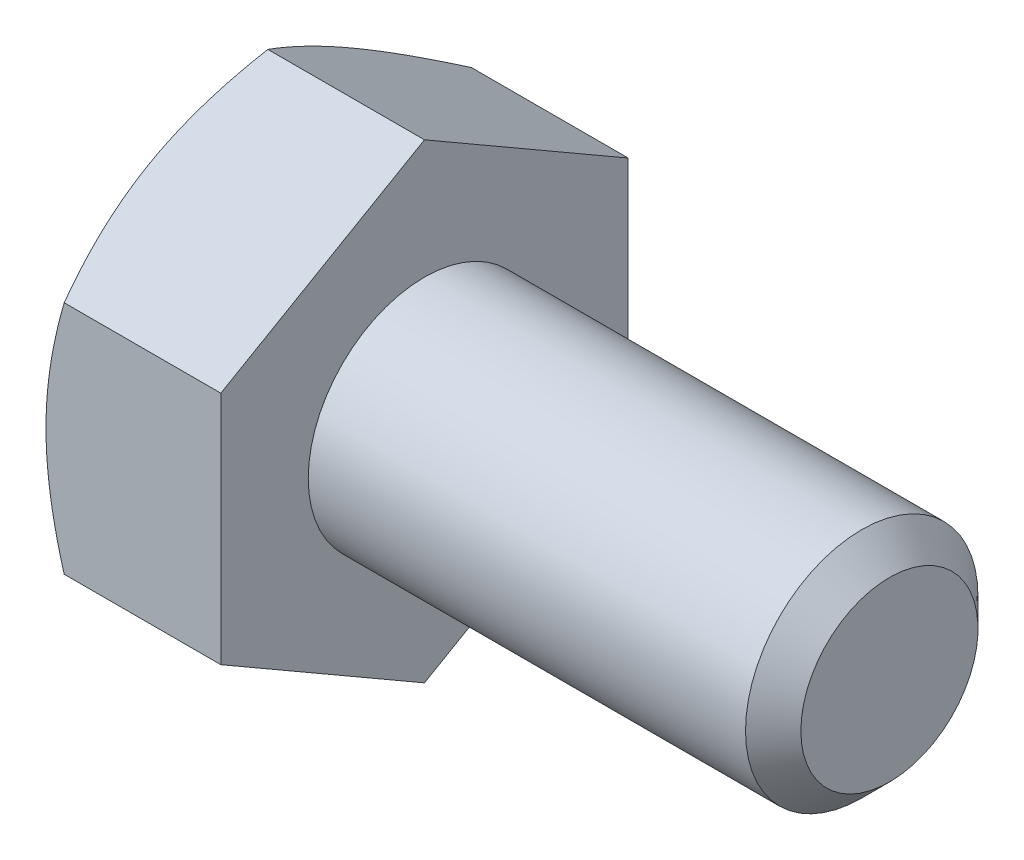
SolidWorks part; units mm, degrees
extrude "BaseHead" add sketch "Sketch1" along normal blind 4.7752
sketch "Sketch1" plane through (0, 0, 0) normal (1, 0, 0) x (0, 0, -1)
  line L0 (5.5626, 3.2116) -> (5.5626, -3.2116)
  line L1 (-5.5626, 3.2116) -> (-5.5626, -3.2116)
  line L2 (5.5626, -3.2116) -> (0, -6.4231)
  line L3 (0, -6.4231) -> (-5.5626, -3.2116)
  line L4 (5.5626, 3.2116) -> (0, 6.4231)
  line L5 (0, 6.4231) -> (-5.5626, 3.2116)
  dimension "Width_flats" = 11.1252
  dimension "D2" = 120
  dimension "D3" = 5.5626
  dimension "D4" = 5.5626
  dimension "D5" = 5.5626
ref_plane "Plane1" through (0, 0, 0) normal (0, 0, 1) x (1, 0, 0)
ref_plane "Plane2" through (0, 0, 0) normal (0, 1, 0) x (1, 0, 0)
ref_plane "Plane3" through (0, 0, 0) normal (1, 0, 0) x (0, 0, -1)
sketch "BodySke" plane through (0, 0, 0) normal (0, 0, 1) x (1, 0, 0)
  line L0 (0, 3.2116) -> (0, -3.2116) construction
  line L1 (0, 0) -> (17.4752, 0)
  line L2 (0, 0) -> (0, 3.175)
  line L3 (0, 3.175) -> (16.7195, 3.175)
  line L4 (17.4752, 0) -> (17.4752, 2.4193)
  line L5 (4.7752, 6.4231) -> (4.7752, 3.2116) construction
  line L6 (17.4752, 2.4193) -> (16.7195, 3.175)
  line L7 (0, 0) -> (96.52, 0) construction
  line L8 (17.4752, -2.4193) -> (16.7195, -3.175) construction
  line L9 (0, -3.175) -> (16.7195, -3.175) construction
  line L10 (6.0452, 15.24) -> (6.0452, -2.54) construction
  line L11 (4.7752, 15.24) -> (4.7752, -2.54) construction
  line L12 (4.7752, 3.2116) -> (4.7752, -3.2116) construction
  dimension "Diameter" = 6.35
  dimension "Advance" = 1.27
revolve "BaseBody" add sketch "BodySke" angle 360 about L7
cosmetic thread "ThreadCosmetic" [suppressed] parameters "Thread_length"=11.43, "Thread_minor"=4.8387
sketch "Sketch3" plane through (0, 0, 0) normal (0, 0, 1) x (1, 0, 0)
  line L0 (0, 5.5626) -> (4.163, 12.7731)
  line L1 (0, 6.4231) -> (0, 3.2116) construction
  line L2 (4.163, 12.7731) -> (4.163, 19.1231)
  line L3 (4.163, 19.1231) -> (-12.7, 19.1231)
  line L4 (-12.7, 19.1231) -> (-12.7, 5.5626)
  line L5 (-12.7, 5.5626) -> (0, 5.5626)
  line L6 (0, 0) -> (99.06, 0) construction
  line L7 (4.7752, 6.4231) -> (0, 6.4231) construction
  dimension "D1" = 5.5626
  dimension "D2" = 6.35
  dimension "D3" = 12.7
  dimension "D4" = 6.35
  dimension "Head_ch_ang" = 30
revolve "HeadChamfer" cut sketch "Sketch3" angle 360 about L6
fillet "HeadFillet" [suppressed] radius 0.762
sketch "ThdSchSke" plane through (0, 0, 0) normal (0, 0, 1) x (1, 0, 0)
  line L0 (6.0452, -2.4194) -> (5.5161, -3.175)
  line L1 (6.0452, -2.4194) -> (6.5743, -3.175)
  line L2 (6.5743, -3.175) -> (6.5743, -3.9688)
  line L3 (-3.175, 0) -> (5.1513, 0) construction
  line L5 (6.5743, -3.9688) -> (5.5161, -3.9688)
  line L6 (5.5161, -3.9688) -> (5.5161, -3.175)
  dimension "Thread_minor" = 4.8387
  dimension "Diameter" = 6.35
  dimension "Start" = 6.0452
revolve "ThreadSchematic" [suppressed] cut sketch "ThdSchSke" angle 360 about L3
pattern_linear "ThdSchPat" [suppressed]
equation "\"D3@Sketch1\" = \"Width_flats@Sketch1\" / 2"
equation "\"D4@Sketch1\" = \"D3@Sketch1\""
equation "\"D5@Sketch1\" = \"D4@Sketch1\""
equation "\"Thread_minor@ThreadCosmetic\" = \"Minor_dia@BodySke\""
equation "\"D1@Sketch3\" = \"Width_flats@Sketch1\" / 2"
equation "\"Thread_length@ThreadCosmetic\" = ((sgn( (\"Length@BodySke\" - \"Advance@BodySke\" ) - \"Thread_nom@BodySke\" )-1)*( (\"Length@BodySke\" - \"Advance@BodySke\" ) - \"Thread_nom@BodySke\" ))/-2+ \"Thread_nom@BodySke\""
equation "\"Thread_minor@ThdSchSke\" = \"Minor_dia@BodySke\""
equation "\"Diameter@ThdSchSke\" = \"Diameter@BodySke\""
equation "\"Overcut@ThdSchSke\" = \"Diameter@BodySke\" * 1.25"
equation "\"Start@ThdSchSke\" = \"Head_ht@BaseHead\" + \"Length@BodySke\" - \"Thread_length@ThreadCosmetic\"  '---Non-countersunk---"
equation "\"Num_threads@ThdSchPat\" = int( \"Thread_length@ThreadCosmetic\" / \"Advance@BodySke\" + 0.999 )  + 1"
equation "\"Advance@ThdSchPat\" = \"Thread_length@ThreadCosmetic\" /  (\"Num_threads@ThdSchPat\" - 1) 'relax it"
equation "\"Num_threads@ThdSchPat\" = \"Num_threads@ThdSchPat\" - sgn( \"Num_threads@ThdSchPat\" - 1) '---chamfered tips only---"
